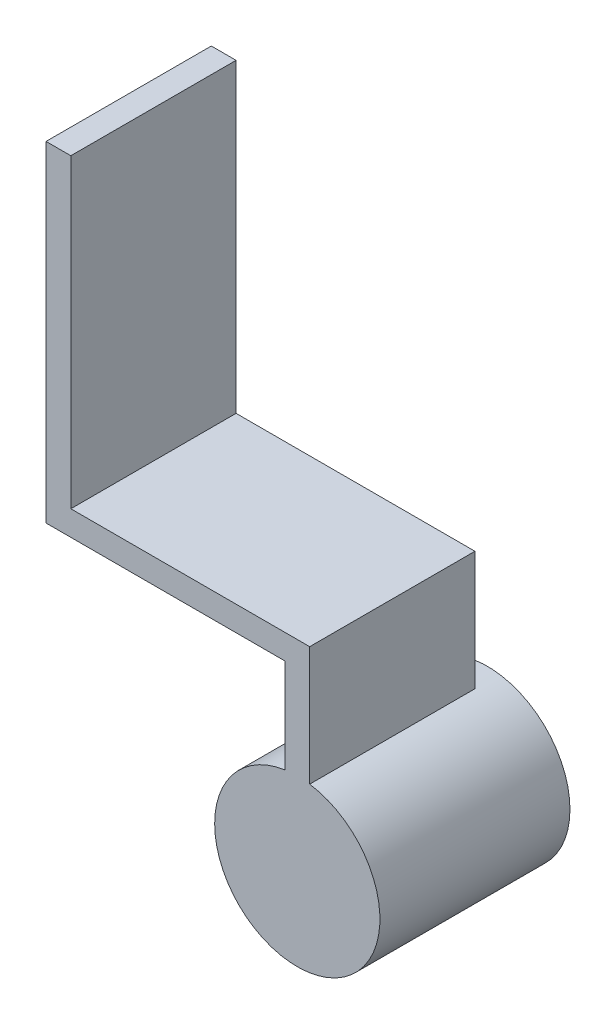
SolidWorks part; units mm, degrees
ref_plane "Front Plane" through (0, 0, 0) normal (0, 0, 1) x (1, 0, 0)
ref_plane "Top Plane" through (0, 0, 0) normal (0, 1, 0) x (1, 0, 0)
ref_plane "Right Plane" through (0, 0, 0) normal (1, 0, 0) x (0, 0, -1)
sketch "Sketch1" plane through (0, 0, 0) normal (0, 0, 1) x (1, 0, 0)
  line L6 (0, 0) -> (0, -27.999)
  line L7 (-3, -2.999) -> (-3, -27.999)
  line L8 (0, -27.999) -> (-3, -27.999)
  line L10 (-3, -2.999) -> (-31.9076, -2.999)
  line L11 (-31.9076, -2.999) -> (-31.9076, 37.001)
  line L13 (-28.9076, 0) -> (-28.9076, 37.001)
  line L14 (-28.9076, 37.001) -> (-31.9076, 37.001)
  line L16 (0, 0) -> (-2.9244, 0) construction
  line L17 (-3, -2.999) -> (-3, -2.999) construction
  line L18 (-28.9076, 0) -> (0, 0)
  dimension "D1" = 3
  dimension "D2" = 2.999
  dimension "D3" = 25
  dimension "D4" = 40
  dimension "D5" = 28.9076
  dimension "D6" = 3
extrude "Boss-Extrude1" add sketch "Sketch1" along normal blind 20
sketch "Sketch4" plane through (0, 0, 0) normal (0, 0, -1) x (-1, 0, 0)
  line L0 (3, -27.999) -> (0, -27.999) construction
  line L1 (0, -27.999) -> (0, 0) construction
  circle A0 centre (1.5, -24.299) radius 10
  dimension "D1" = 20
  dimension "D2" = 3.7
  dimension "D3" = 1.5
extrude "Boss-Extrude2" add sketch "Sketch4" along normal blind 3 and the other way up to surface
